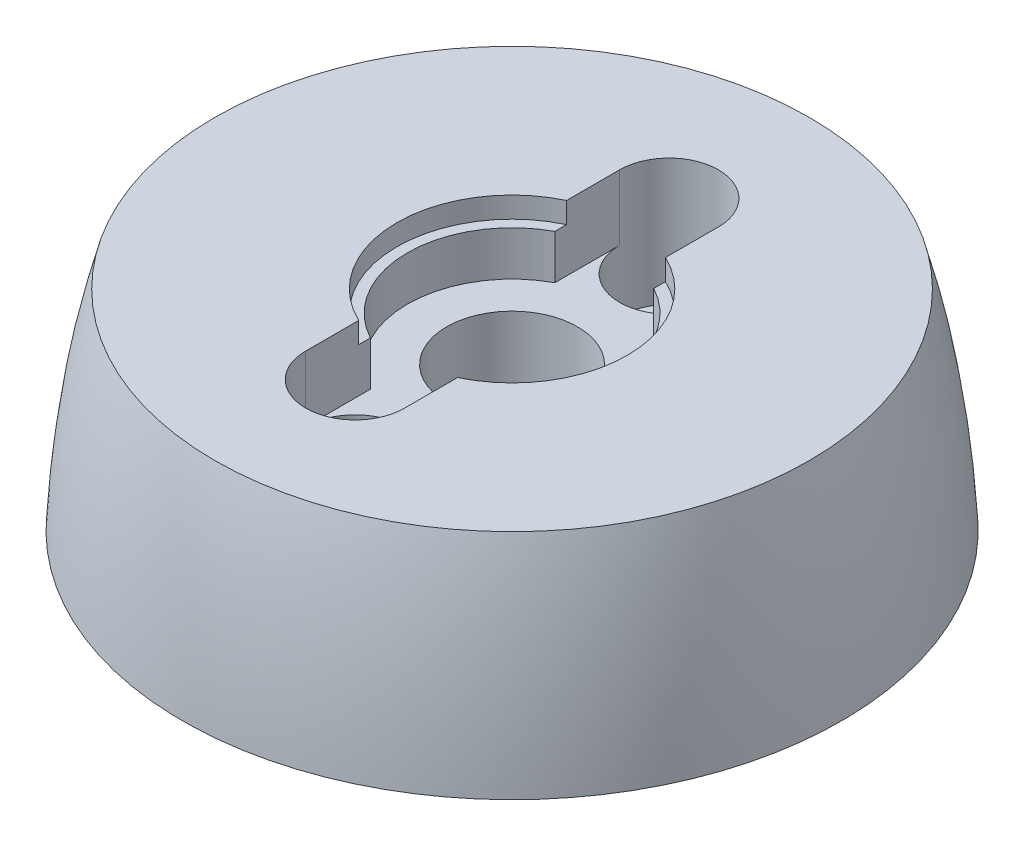
SolidWorks part; units mm, degrees
ref_plane "前视" through (0, 0, 0) normal (0, 0, 1) x (1, 0, 0)
ref_plane "上视" through (0, 0, 0) normal (0, 1, 0) x (1, 0, 0)
ref_plane "右视" through (0, 0, 0) normal (1, 0, 0) x (0, 0, -1)
sketch "草图1" plane through (0, 0, 0) normal (0, 0, 1) x (1, 0, 0)
  line L0 (0, 0) -> (0, 62.5433) construction
  line L1 (0, 0) -> (0, 31.75)
  line L2 (5.4775, 31.75) -> (0, 31.75)
  line L4 (0, 0) -> (20, 0)
  spline S0 degree 3 poles (5.4775, 31.75) (16.2416, 23.8743) (19.4067, 11.2195) (20, 0) knots 0.132415 0.132415 0.132415 0.132415 1 1 1 1
  dimension "D1" = 20
  dimension "D2" = 31.75
  dimension "D3" = 0
revolve "旋转1" add sketch "草图1" angle 360 about L0
ref_plane "基准面1" through (0, 40, 0) normal (0, -1, 0) x (-1, 0, 0)
hole_wizard "CBORE for M3 Hex Head Bolt1" positions "草图3" profile "草图2" counterbore size "M3" standard "GB" end condition up to next
sketch "草图3" plane through (0, 40, 0) normal (0, -1, 0) x (-1, 0, 0)
  line L0 (0, 9.525) -> (0, -9.525) construction
  point P0 (0, 9.525)
  point P2 (0, -9.525)
  dimension "D1" = 19.05
sketch "草图2" plane through (0, 40, -9.525) normal (1, 0, 0) x (0, 0, 1)
  line L0 (0, 0) -> (0, 40)
  line L1 (0, 40) -> (1.7, 40)
  line L3 (1.7, 40) -> (1.7, 35)
  line L4 (1.7, 35) -> (3, 35)
  line L5 (3, 35) -> (3, 0)
  line L7 (3, 0) -> (0, 0)
  line L11 (0, -6.35) -> (0, 107.95) construction
  dimension "通孔孔直径" = 3.4
  dimension "通孔孔深度" = 40
  dimension "柱形沉头孔直径" = 6
  dimension "柱形沉头孔深度" = 35
sketch "Sketch1" plane through (0, 0, 0) normal (0, 0, 1) x (1, 0, 0)
  line L1 (-22.7304, 50.8) -> (22.7304, 50.8)
  line L2 (-22.7304, 50.8) -> (-22.7304, 12.7)
  line L3 (-22.7304, 12.7) -> (22.7304, 12.7)
  line L4 (22.7304, 50.8) -> (22.7304, 12.7)
  line L5 (-22.7304, 50.8) -> (22.7304, 12.7) construction
  line L6 (-22.7304, 12.7) -> (22.7304, 50.8) construction
  line L7 (-20, 0) -> (20, 0) construction
  line L8 (5.4775, 31.75) -> (-5.4775, 31.75) construction
  point P0 (0, 31.75)
  point P5 (0, 31.75)
  dimension "D1" = 12.7
extrude "Cut-Extrude1" cut sketch "Sketch1" against normal through all and the other way through all
sketch "Sketch2" plane through (0, 12.7, 0) normal (0, 1, 0) x (1, 0, 0)
  line L0 (-3, 9.525) -> (-3, 5.5967)
  line L1 (3, 9.525) -> (3, 5.5967)
  line L2 (-3, -9.525) -> (-3, -5.5967)
  line L3 (3, -9.525) -> (3, -5.5967)
  arc A0 (-3, 5.5967) -> (-3, -5.5967) centre (0, 0) ccw
  arc A1 (3, 9.525) -> (-3, 9.525) centre (0, 9.525) ccw
  circle A2 centre (0, 9.525) radius 3 construction
  arc A3 (-3, -9.525) -> (3, -9.525) centre (0, -9.525) ccw
  circle A4 centre (0, -9.525) radius 3 construction
  arc A5 (3, -5.5967) -> (3, 5.5967) centre (0, 0) ccw
  dimension "D1" = 12.7
extrude "Cut-Extrude2" cut sketch "Sketch2" against normal blind 3.9688
sketch "Sketch3" plane through (0, 12.7, 0) normal (0, 1, 0) x (1, 0, 0)
  circle A0 centre (0, 0) radius 6.985
  dimension "D1" = 13.97
extrude "Cut-Extrude3" cut sketch "Sketch3" against normal blind 1.27
sketch "Sketch4" plane through (0, 8.7312, 0) normal (0, 1, 0) x (1, 0, 0)
  circle A0 centre (0, 0) radius 3.9688
  dimension "D1" = 7.9375
extrude "Cut-Extrude4" cut sketch "Sketch4" against normal through all
